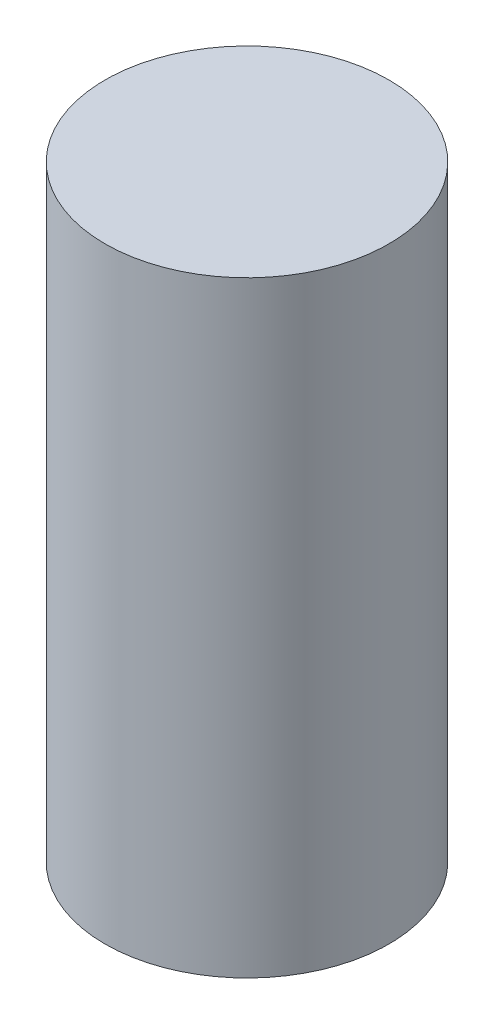
SolidWorks part; units mm, degrees
ref_plane "Front Plane" through (0, 0, 0) normal (0, 0, 1) x (1, 0, 0)
ref_plane "Top Plane" through (0, 0, 0) normal (0, 1, 0) x (1, 0, 0)
ref_plane "Right Plane" through (0, 0, 0) normal (1, 0, 0) x (0, 0, -1)
sketch "Sketch1" plane through (0, 0, 0) normal (0, 1, 0) x (1, 0, 0)
  circle A0 centre (138.3167, -27.9357) radius 13.3783
  point P2 (151.6667, -28.8061)
extrude "Boss-Extrude1" add sketch "Sketch1" along normal blind 57.1437
move or copy body "Body-Move/Copy1" [suppressed] bodies to move or copy 101
